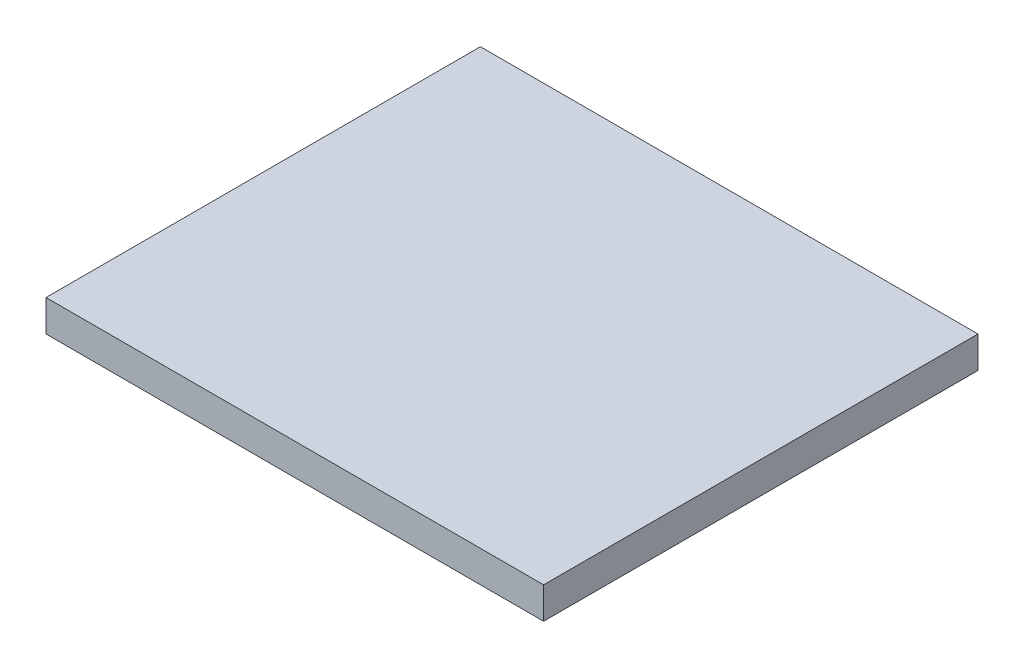
SolidWorks part; units mm, degrees
ref_plane "Front Plane" through (0, 0, 0) normal (0, 0, 1) x (1, 0, 0)
ref_plane "Top Plane" through (0, 0, 0) normal (0, 1, 0) x (1, 0, 0)
ref_plane "Right Plane" through (0, 0, 0) normal (1, 0, 0) x (0, 0, -1)
sketch "Sketch1" plane through (0, 0, 0) normal (0, 1, 0) x (1, 0, 0)
  line L1 (-31.5, 27.5) -> (31.5, 27.5)
  line L2 (-31.5, 27.5) -> (-31.5, -27.5)
  line L3 (-31.5, -27.5) -> (31.5, -27.5)
  line L4 (31.5, 27.5) -> (31.5, -27.5)
  line L5 (-31.5, 27.5) -> (31.5, -27.5) construction
  line L6 (-31.5, -27.5) -> (31.5, 27.5) construction
  point P0 (0, 0)
  dimension "D1" = 55
  dimension "D2" = 63
extrude "Boss-Extrude1" add sketch "Sketch1" along normal blind 4
